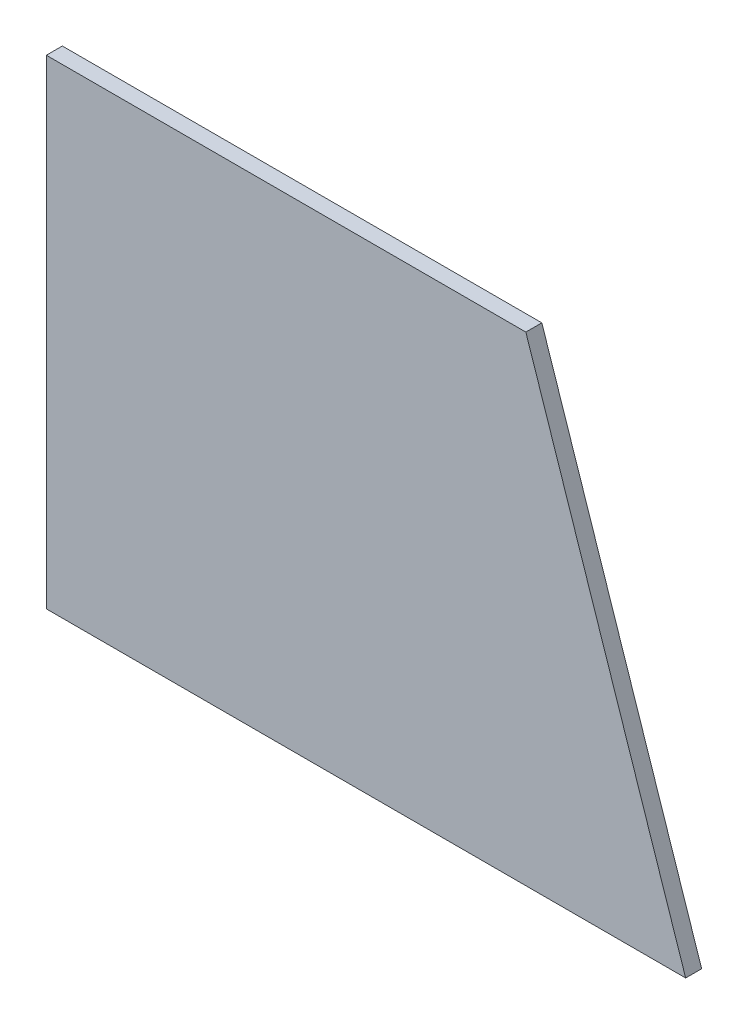
SolidWorks part; units mm, degrees
ref_plane "Front Plane" through (0, 0, 0) normal (0, 0, 1) x (1, 0, 0)
ref_plane "Top Plane" through (0, 0, 0) normal (0, 1, 0) x (1, 0, 0)
ref_plane "Right Plane" through (0, 0, 0) normal (1, 0, 0) x (0, 0, -1)
sketch "Sketch1" plane through (0, 0, 0) normal (0, 0, 1) x (1, 0, 0)
  line L0 (0, 0.6) -> (0, 0)
  line L1 (0, 0) -> (0.8, 0)
  line L2 (0.8, 0) -> (0.6, 0.6)
  line L3 (0.6, 0.6) -> (0, 0.6)
  dimension "D1" = 0.6
  dimension "D2" = 0.8
extrude "Boss-Extrude1" add sketch "Sketch1" along normal mid plane 0.02
